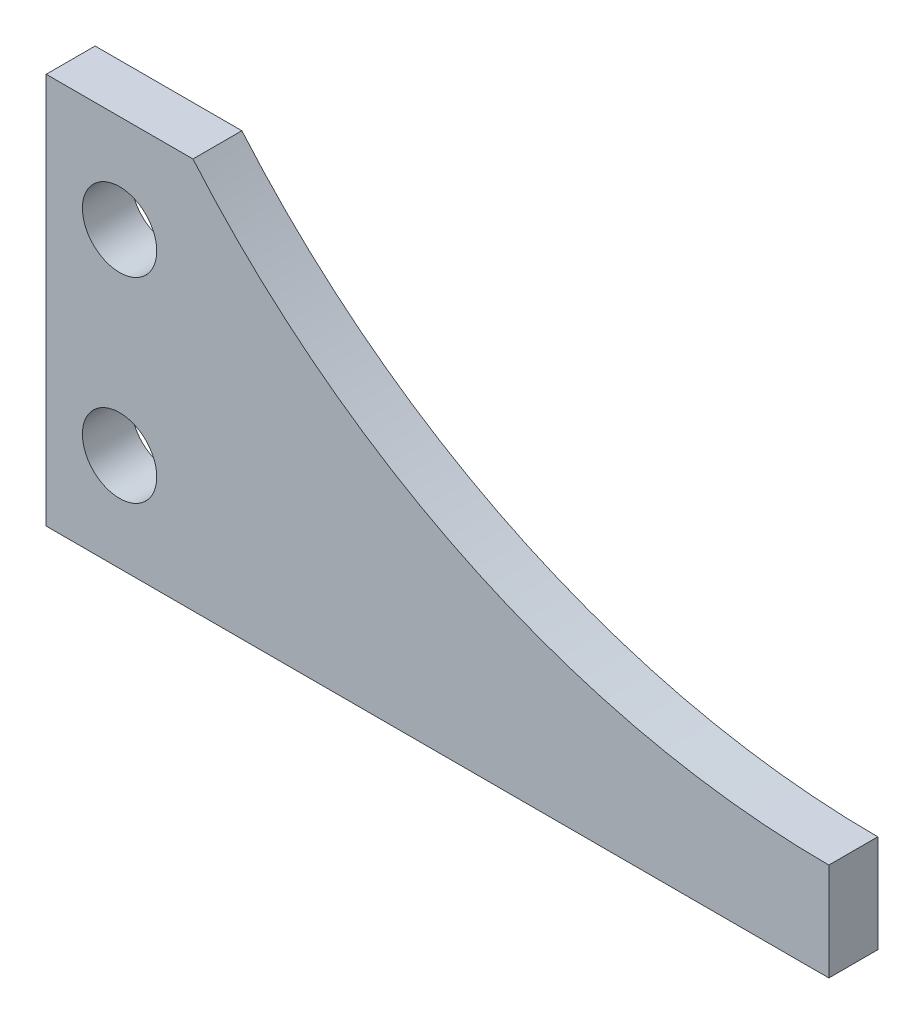
SolidWorks part; units mm, degrees
ref_plane "Front Plane" through (0, 0, 0) normal (0, 0, 1) x (1, 0, 0)
ref_plane "Top Plane" through (0, 0, 0) normal (0, 1, 0) x (1, 0, 0)
ref_plane "Right Plane" through (0, 0, 0) normal (1, 0, 0) x (0, 0, -1)
sketch "Sketch1" plane through (0, 0, 0) normal (0, 0, 1) x (1, 0, 0)
  line L0 (0, 0) -> (0, 25.4)
  line L1 (0, 25.4) -> (9.525, 25.4)
  line L2 (0, 0) -> (50.8, 0)
  line L3 (50.8, 0) -> (50.8, 6.35)
  line L4 (50.8, 6.35) -> (0, 6.35) construction
  line L5 (4.7625, 0) -> (4.7625, 6.35) construction
  line L6 (4.7625, 6.35) -> (4.7625, 19.05) construction
  line L7 (4.7625, 19.05) -> (4.7625, 25.4) construction
  arc A0 (9.525, 25.4) -> (50.8, 6.35) centre (50.8, 60.5896) ccw
  circle A1 centre (4.7625, 6.35) radius 2.413
  circle A2 centre (4.7625, 19.05) radius 2.413
  dimension "D4" = 4.826
  dimension "radius" = 50.8
  dimension "D1" = 6.35
  dimension "D2" = 9.525
  dimension "D3" = 25.4
  dimension "D5" = 6.35
  dimension "D6" = 6.35
extrude "Boss-Extrude1" add sketch "Sketch1" along normal blind 3.175
equation "\"Radius\"= 2in"
equation "\"Exit Height\"= 0.25in"
equation "\"radius@Sketch1\"=\"Radius\""
equation "\"Inlet Diameter\" = 3 / 4"
equation "\"D2@Sketch1\"=\"Inlet Diameter\"/2"
equation "\"Impeller Height\"= 1in"
equation "\"D3@Sketch1\"=\"Impeller Height\""
